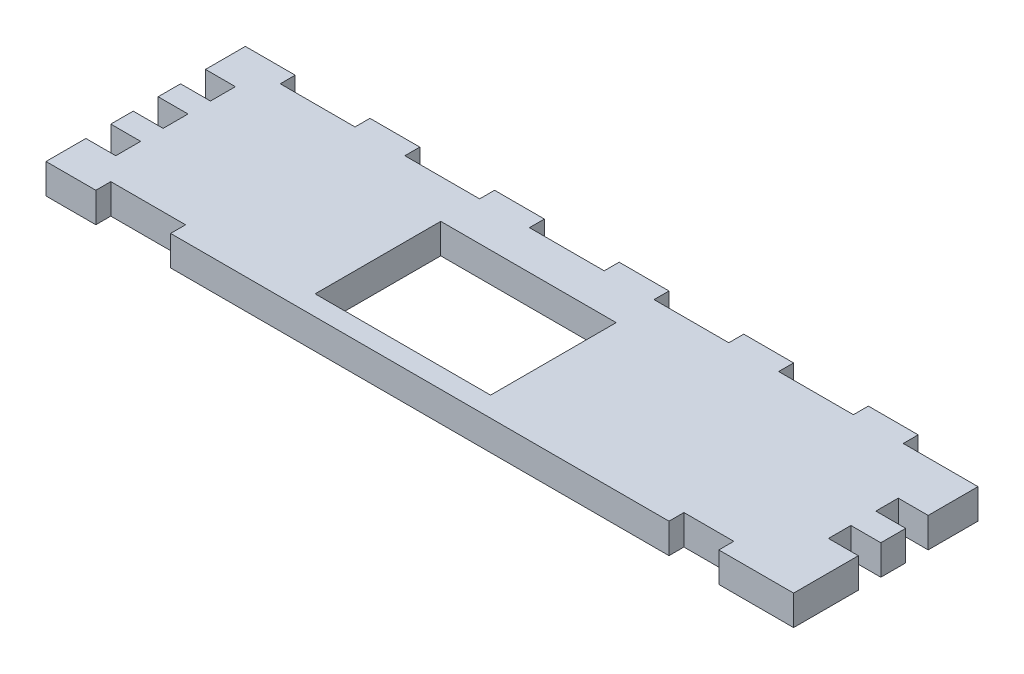
SolidWorks part; units mm, degrees
ref_plane "Спереди" through (0, 0, 0) normal (0, 0, 1) x (1, 0, 0)
ref_plane "Сверху" through (0, 0, 0) normal (0, 1, 0) x (1, 0, 0)
ref_plane "Справа" through (0, 0, 0) normal (1, 0, 0) x (0, 0, -1)
sketch "Эскиз1" plane through (0, 0, 0) normal (0, 1, 0) x (1, 0, 0)
  line L1 (0, 0) -> (150, 0)
  line L2 (0, 0) -> (0, -36)
  line L3 (0, -36) -> (150, -36)
  line L4 (150, 0) -> (150, -36)
  dimension "D1" = 36
  dimension "D2" = 150
extrude "Бобышка-Вытянуть2" add sketch "Эскиз1" along normal blind 6
sketch "Эскиз6" plane through (0, 0, 0) normal (0, 0, -1) x (-1, 0, 0)
  line L0 (22, 0) -> (-22, 0) construction
  line L1 (0, 6) -> (-10, 6)
  line L2 (0, 6) -> (0, 0)
  line L3 (0, 0) -> (-10, 0)
  line L4 (-10, 6) -> (-10, 0)
  dimension "D1" = 10
extrude "Бобышка-Вытянуть4" add sketch "Эскиз6" along normal blind 4
pattern_linear "Линейный массив1" count 6 spacing 25 along (1, 0, 0) of "Бобышка-Вытянуть4"
sketch "Эскиз8" plane through (0, 0, 0) normal (-1, 0, 0) x (0, 0, 1)
  line L0 (-4, 6) -> (36, 6) construction
  line L1 (4, 6) -> (9, 6)
  line L2 (4, 6) -> (4, 0)
  line L3 (4, 0) -> (9, 0)
  line L4 (9, 6) -> (9, 0)
  line L5 (-4, 0) -> (36, 0) construction
  line L6 (-4, 0) -> (-4, 6) construction
  line L7 (13.5, 6) -> (18.5, 6)
  line L8 (13.5, 6) -> (13.5, 0)
  line L9 (13.5, 0) -> (18.5, 0)
  line L10 (18.5, 6) -> (18.5, 0)
  line L11 (23.0048, 6) -> (28, 6)
  line L12 (23.0048, 6) -> (23.0048, 0)
  line L13 (23.0048, 0) -> (28, 0)
  line L14 (28, 6) -> (28, 0)
  line L15 (36, 6) -> (36, 0) construction
  dimension "D1" = 5
  dimension "D2" = 5
  dimension "D3" = 4.9952
  dimension "D4" = 8
  dimension "D5" = 8
  dimension "D6" = 4.5
extrude "Вырез-Вытянуть3" cut sketch "Эскиз8" against normal blind 6
sketch "Эскиз9" plane through (0, 6, 0) normal (0, 1, 0) x (1, 0, 0)
  line L0 (6, -4) -> (150, -4) construction
  line L1 (150, -36) -> (150, 0) construction
  line L2 (6, -9) -> (150, -9) construction
  line L3 (6, -13.5) -> (150, -13.5) construction
  line L4 (6, -18.5) -> (150, -18.5) construction
  line L5 (6, -23.0048) -> (150, -23.0048) construction
  line L6 (6, -28) -> (150, -28) construction
sketch "Эскиз11" plane through (150, 0, 0) normal (1, 0, 0) x (0, 0, -1)
  line L0 (-23.0048, 6) -> (-23.0048, 0) construction
  line L5 (22, 0) -> (-22, 0) construction
  line L6 (-18.5, 6) -> (-18.5, 0) construction
  line L7 (-36, 0) -> (0, 0) construction
  line L8 (-13.5, 6) -> (-13.5, 0) construction
  line L9 (-9, 6) -> (-9, 0) construction
  line L11 (-23.0048, 6) -> (-18.5, 6)
  line L12 (-23.0048, 6) -> (-23.0048, 0)
  line L13 (-23.0048, 0) -> (-18.5, 0)
  line L14 (-18.5, 6) -> (-18.5, 0)
  line L15 (-13.5, 6) -> (-9, 6)
  line L16 (-13.5, 6) -> (-13.5, 0)
  line L17 (-13.5, 0) -> (-9, 0)
  line L18 (-9, 6) -> (-9, 0)
extrude "Вырез-Вытянуть4" cut sketch "Эскиз11" against normal blind 6
sketch "Эскиз12" plane through (0, 6, 0) normal (0, 1, 0) x (1, 0, 0)
  line L0 (0, -18.5) -> (0, -23.0048) construction
  line L1 (50, -6.8) -> (85.2, -6.8)
  line L2 (50, -6.8) -> (50, -32)
  line L3 (50, -32) -> (85.2, -32)
  line L4 (85.2, -6.8) -> (85.2, -32)
  line L5 (0, -36) -> (150, -36) construction
  dimension "D1" = 35.2
  dimension "D2" = 25.2
  dimension "D3" = 50
  dimension "D4" = 4
extrude "Вырез-Вытянуть5" cut sketch "Эскиз12" against normal through all
sketch "Эскиз13" plane through (0, 6, 0) normal (0, 1, 0) x (1, 0, 0)
  line L0 (10, 0) -> (10, -36) construction
  line L1 (0, -36) -> (150, -36) construction
  line L2 (25, 0) -> (25, -36) construction
  line L3 (125, 0) -> (125, -36) construction
  line L4 (135, 0) -> (135, -36) construction
sketch "Эскиз14" plane through (0, 0, 36) normal (0, 0, 1) x (1, 0, 0)
  line L0 (0, 0) -> (150, 0) construction
  line L1 (10, 6) -> (25, 6)
  line L2 (10, 6) -> (10, 0)
  line L3 (10, 0) -> (25, 0)
  line L4 (25, 6) -> (25, 0)
  line L6 (125, 6) -> (135, 6)
  line L7 (125, 6) -> (125, 0)
  line L8 (125, 0) -> (135, 0)
  line L9 (135, 6) -> (135, 0)
  dimension "D1" = 15
  dimension "D2" = 10
extrude "Вырез-Вытянуть6" cut sketch "Эскиз14" against normal blind 4
sketch "Эскиз15" plane through (0, 0, 0) normal (0, 0, -1) x (-1, 0, 0)
  line L1 (-25, 6) -> (-10, 6)
  line L2 (-25, 6) -> (-25, 0)
  line L3 (-25, 0) -> (-10, 0)
  line L4 (-10, 6) -> (-10, 0)
extrude "Бобышка-Вытянуть5" add sketch "Эскиз15" along normal blind 1
pattern_linear "Линейный массив2" count 5 spacing 25 along (1, 0, 0) of "Бобышка-Вытянуть5"
sketch "Эскиз16" plane through (0, 0, 0) normal (0, 0, -1) x (-1, 0, 0)
  line L1 (-150, 6) -> (-135, 6)
  line L2 (-150, 6) -> (-150, 0)
  line L3 (-150, 0) -> (-135, 0)
  line L4 (-135, 6) -> (-135, 0)
extrude "Бобышка-Вытянуть6" add sketch "Эскиз16" along normal blind 1
sketch "Эскиз17" plane through (0, 0, 32) normal (0, 0, 1) x (1, 0, 0)
  line L0 (22, 0) -> (-22, 0) construction
  line L1 (125, 6) -> (135, 6)
  line L2 (125, 6) -> (125, 0)
  line L3 (125, 0) -> (135, 0)
  line L4 (135, 6) -> (135, 0)
  line L5 (135, 0) -> (135, 6) construction
extrude "Бобышка-Вытянуть7" add sketch "Эскиз17" along normal blind 1
sketch "Эскиз18" plane through (0, 0, 32) normal (0, 0, 1) x (1, 0, 0)
  line L0 (22, 0) -> (-22, 0) construction
  line L1 (10, 6) -> (25, 6)
  line L2 (10, 6) -> (10, 0)
  line L3 (10, 0) -> (25, 0)
  line L4 (25, 6) -> (25, 0)
  line L5 (25, 0) -> (25, 6) construction
extrude "Бобышка-Вытянуть8" add sketch "Эскиз18" along normal blind 1
